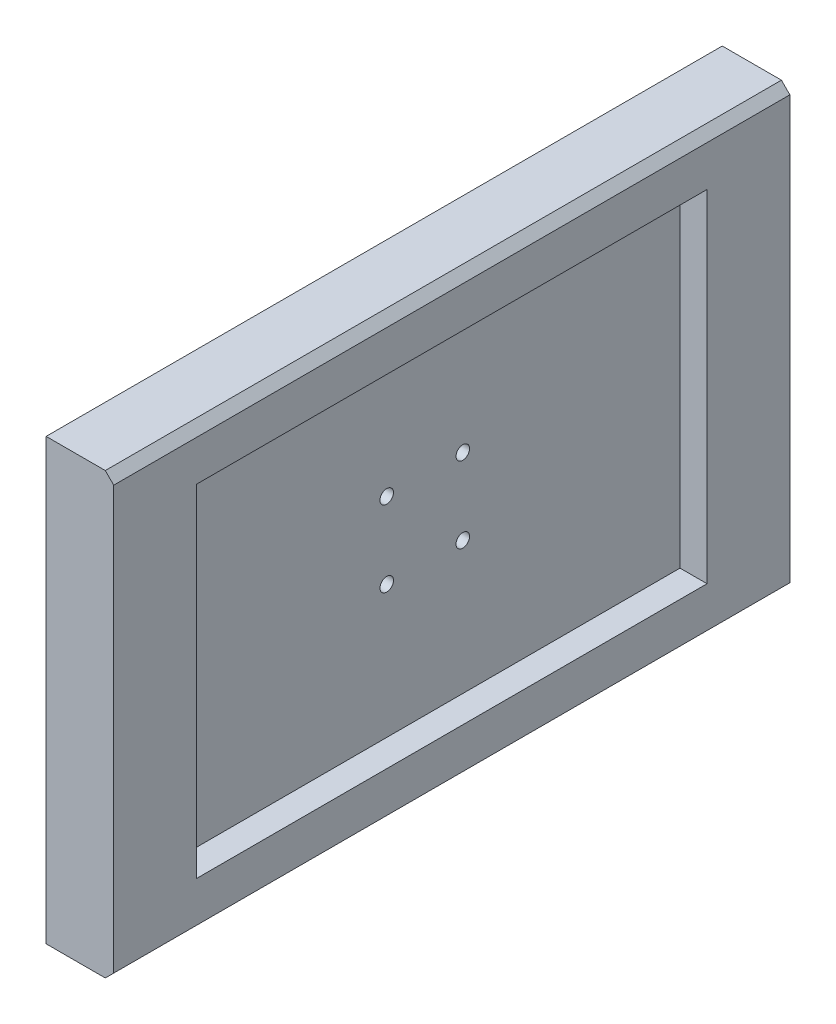
SolidWorks part; units mm, degrees
material "ABS"
ref_plane "Front Plane" through (0, 0, 0) normal (0, 0, 1) x (1, 0, 0)
ref_plane "Top Plane" through (0, 0, 0) normal (0, 1, 0) x (1, 0, 0)
ref_plane "Right Plane" through (0, 0, 0) normal (1, 0, 0) x (0, 0, -1)
ref_plane "X_WEB" through (33.5, 0, 0) normal (1, 0, 0) x (0, 0, -1)
sketch "Sketch1" plane through (33.5, 0, 0) normal (1, 0, 0) x (0, 0, -1)
  line L1 (-40, -26) -> (40, -26)
  line L2 (-40, -26) -> (-40, 26)
  line L3 (-40, 26) -> (40, 26)
  line L4 (40, -26) -> (40, 26)
extrude "Boss-Extrude1" add sketch "Sketch1" along normal blind 8
sketch "Sketch2" plane through (33.5, 0, 0) normal (1, 0, 0) x (0, 0, -1)
  circle A0 centre (-4.5, -4.5) radius 0.8
  circle A1 centre (4.5, -4.5) radius 0.8
  circle A2 centre (-4.5, 4.5) radius 0.8
  circle A3 centre (4.5, 4.5) radius 0.8
extrude "Cut-Extrude2" cut sketch "Sketch2" along normal blind 5
ref_plane "X_SOLE" through (41.5, 0, 0) normal (1, 0, 0) x (0, 0, -1)
sketch "Sketch3" plane through (41.5, 0, 0) normal (1, 0, 0) x (0, 0, -1)
  line L1 (-30.2, -20.2) -> (30.2, -20.2)
  line L2 (-30.2, -20.2) -> (-30.2, 20.2)
  line L3 (-30.2, 20.2) -> (30.2, 20.2)
  line L4 (30.2, -20.2) -> (30.2, 20.2)
extrude "Cut-Extrude3" cut sketch "Sketch3" against normal blind 3.2
chamfer "Chamfer1" distance 1 angle 45 2 edges at (41.5, -26, 0) (41.5, 26, 0)
